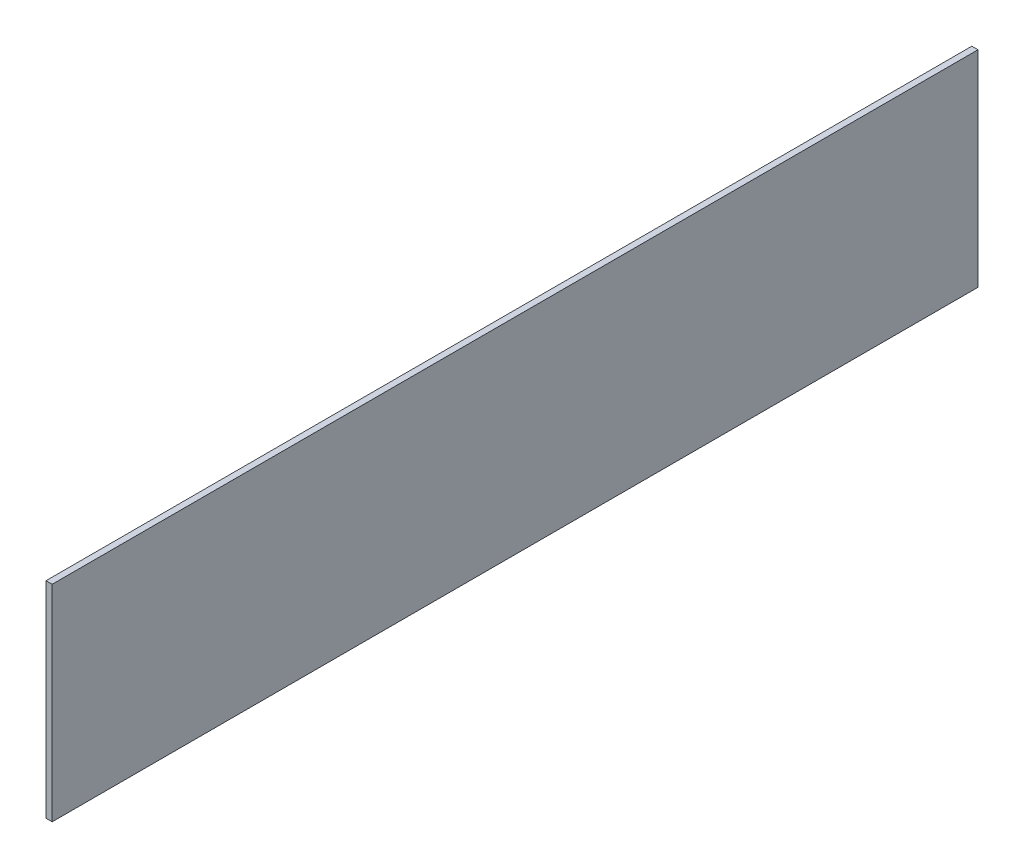
SolidWorks part; units mm, degrees
ref_plane "Front Plane" through (0, 0, 0) normal (0, 0, 1) x (1, 0, 0)
ref_plane "Top Plane" through (0, 0, 0) normal (0, 1, 0) x (1, 0, 0)
ref_plane "Right Plane" through (0, 0, 0) normal (1, 0, 0) x (0, 0, -1)
sketch "Sketch1" plane through (0, 0, 0) normal (1, 0, 0) x (0, 0, -1)
  line L1 (-225, 50) -> (225, 50)
  line L2 (-225, 50) -> (-225, -50)
  line L3 (-225, -50) -> (225, -50)
  line L4 (225, 50) -> (225, -50)
  line L5 (-225, 50) -> (225, -50) construction
  line L6 (-225, -50) -> (225, 50) construction
  point P0 (0, 0)
  dimension "D1" = 450
  dimension "D2" = 100
extrude "Boss-Extrude1" add sketch "Sketch1" along normal blind 3
